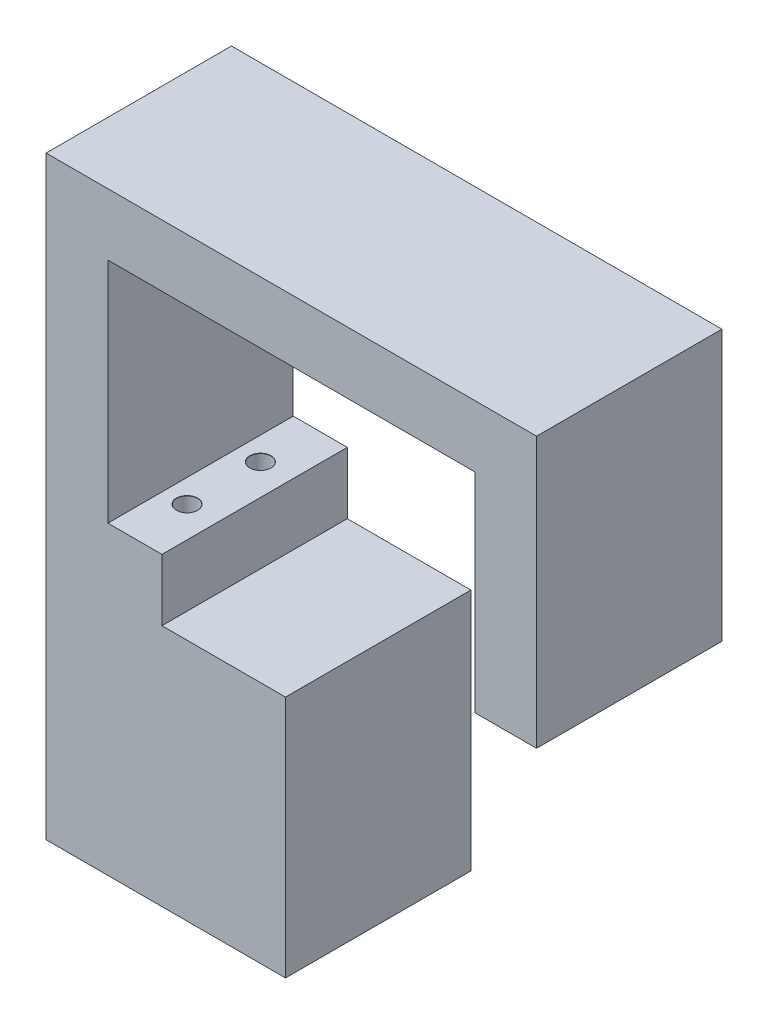
SolidWorks part; units mm, degrees
ref_plane "Front Plane" through (0, 0, 0) normal (0, 0, 1) x (1, 0, 0)
ref_plane "Top Plane" through (0, 0, 0) normal (0, 1, 0) x (1, 0, 0)
ref_plane "Right Plane" through (0, 0, 0) normal (1, 0, 0) x (0, 0, -1)
sketch "Sketch1" plane through (0, 0, 0) normal (0, 0, 1) x (1, 0, 0)
  line L0 (0, 0) -> (-23, 0)
  line L2 (-23, 39.5) -> (-16, 39.5)
  line L3 (-16, 39.5) -> (-16, 31.5)
  line L4 (-16, 31.5) -> (0, 31.5)
  line L5 (0, 31.5) -> (0, 0)
  line L6 (-23, 39.5) -> (-23, 69)
  line L7 (-23, 69) -> (24.5, 69)
  line L8 (24.5, 69) -> (24.5, 42)
  line L9 (24.5, 42) -> (32.5, 42)
  line L10 (32.5, 42) -> (32.5, 77)
  line L11 (32.5, 77) -> (-23.4049, 77)
  line L12 (-23, 0) -> (-31, 0)
  line L13 (-31, 0) -> (-31, 77)
  line L14 (-31, 77) -> (-23.4049, 77)
  dimension "D1" = 16
  dimension "D2" = 31.5
  dimension "D3" = 8
  dimension "D4" = 8
  dimension "D5" = 7
  dimension "D6" = 29.5
  dimension "D7" = 47.5
  dimension "D8" = 27
  dimension "D9" = 8
  dimension "D10" = 8
extrude "Boss-Extrude1" add sketch "Sketch1" along normal mid plane 24
hole_wizard "Ø2.7 (2.7) Diameter Hole1" positions "Sketch2" profile "Sketch3" hole size "Ø2.7" standard "ANSI Metric"
sketch "Sketch2" plane through (0, 39.5, 0) normal (0, 1, 0) x (1, 0, 0)
  line L0 (-16, -12) -> (-16, 12) construction
  line L1 (32.5, -12) -> (-31, -12) construction
  point P0 (-20, 4.75)
  point P2 (-20, -4.75)
  dimension "D1" = 9.5
  dimension "D2" = 4
  dimension "D3" = 7.25
sketch "Sketch3" plane through (-20, 39.5, -4.75) normal (1, 0, 0) x (0, 0, 1)
  line L0 (0, 0) -> (0, 8.8112)
  line L1 (0, 8.8112) -> (1.35, 8)
  line L2 (1.35, 8) -> (1.35, 0.025)
  line L3 (1.35, 0.025) -> (1.375, 0)
  line L5 (1.375, 0) -> (0, 0)
  line L6 (-1.35, 0.025) -> (-1.375, 0) construction
  line L10 (0, 8.8112) -> (-1.35, 8) construction
  line L11 (0, -6.35) -> (0, 107.95) construction
  dimension "Hole Dia." = 2.7
  dimension "Hole Depth" = 8
  dimension "Near C'Sink Dia." = 2.75
  dimension "Near C'Sink Angle" = 90
  dimension "Drill Angle" = 118
hole_wizard "Ø2.7 (2.7) Diameter Hole2" positions "Sketch4" profile "Sketch5" hole size "Ø2.7" standard "ANSI Metric"
sketch "Sketch4" plane through (0, 42, 0) normal (0, -1, 0) x (-1, 0, 0)
  line L1 (-24.5, 12) -> (-32.5, 12) construction
  line L2 (-24.5, -12) -> (-24.5, 12) construction
  point P0 (-28.5, 4.75)
  point P2 (-28.5, -4.75)
  dimension "D1" = 9.5
  dimension "D2" = 4
  dimension "D3" = 7.25
sketch "Sketch5" plane through (28.5, 42, -4.75) normal (1, 0, 0) x (0, 0, -1)
  line L0 (0, 0) -> (0, 8.8112)
  line L1 (0, 8.8112) -> (1.35, 8)
  line L2 (1.35, 8) -> (1.35, 0.025)
  line L3 (1.35, 0.025) -> (1.375, 0)
  line L5 (1.375, 0) -> (0, 0)
  line L6 (-1.35, 0.025) -> (-1.375, 0) construction
  line L10 (0, 8.8112) -> (-1.35, 8) construction
  line L11 (0, -6.35) -> (0, 107.95) construction
  dimension "Hole Dia." = 2.7
  dimension "Hole Depth" = 8
  dimension "Near C'Sink Dia." = 2.75
  dimension "Near C'Sink Angle" = 90
  dimension "Drill Angle" = 118
